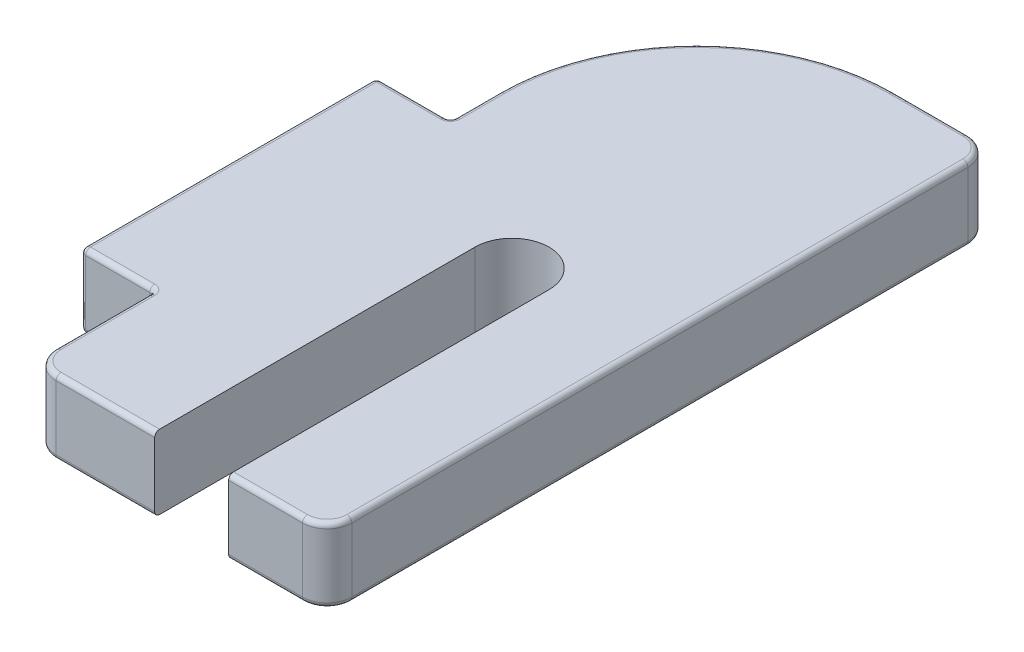
SolidWorks part; units mm, degrees
ref_plane "Front Plane" through (0, 0, 0) normal (0, 0, 1) x (1, 0, 0)
ref_plane "Top Plane" through (0, 0, 0) normal (0, 1, 0) x (1, 0, 0)
ref_plane "Right Plane" through (0, 0, 0) normal (1, 0, 0) x (0, 0, -1)
sketch "Sketch1" plane through (0, 0, 0) normal (0, 1, 0) x (1, 0, 0)
  line L0 (-1.5, 0) -> (-1.5, -13)
  line L1 (1.5, 0) -> (1.5, -13)
  line L2 (1.5, -13) -> (4.5, -13)
  line L3 (5.5, -12) -> (5.5, 13)
  line L4 (4.5, 14) -> (1.5, 14)
  line L5 (-6.5, 6) -> (-6.5, 4)
  line L6 (-6.5, 4) -> (-9.5, 4)
  line L7 (-9.5, 4) -> (-9.5, -8)
  line L8 (-9.5, -8) -> (-6.5, -8)
  line L9 (-6.5, -8) -> (-6.5, -12)
  line L10 (-5.5, -13) -> (-1.5, -13)
  arc A0 (1.5, 0) -> (-1.5, 0) centre (0, 0) ccw
  arc A1 (1.5, 14) -> (-6.5, 6) centre (1.5, 6) ccw
  arc A2 (-6.5, -12) -> (-5.5, -13) centre (-5.5, -12) ccw
  arc A3 (4.5, -13) -> (5.5, -12) centre (4.5, -12) ccw
  arc A4 (5.5, 13) -> (4.5, 14) centre (4.5, 13) ccw
  point P18 (-6.5, -13)
  point P21 (5.5, -13)
  point P24 (5.5, 14)
  dimension "D1" = 1.5
  dimension "D9" = 8
  dimension "D10" = 1
  dimension "D2" = 4
  dimension "D3" = 5
  dimension "D4" = 27
  dimension "D5" = 13
  dimension "D6" = 12
  dimension "D7" = 5
  dimension "D8" = 3
extrude "Boss-Extrude1" add sketch "Sketch1" along normal blind 3
fillet "Fillet1" radius 0.2 30 edges at (-8, 0, 8) (-8, 3, 8) (-8, 0, -4) (-8, 3, -4) (-6.5, 0, 10) (-6.2071, 0, 12.7071) (-6.5, 3, 10) (-6.2071, 3, 12.7071) (3, 0, 13) (5.2071, 0, 12.7071) (-6.5, 0, -5) (-4.1569, 0, -11.6569) (3, 0, -14) (5.2071, 0, -13.7071) (3, 3, 13) (5.2071, 3, 12.7071) (-6.5, 3, -5) (-4.1569, 3, -11.6569) (3, 3, -14) (5.2071, 3, -13.7071) (-9.5, 1.5, -4) (-9.5, 3, 2) (-9.5, 1.5, 8) (-9.5, 0, 2) (-6.5, 1.5, -4) (-6.5, 1.5, 8) (-3.5, 0, 13) (-3.5, 3, 13) (5.5, 0, -0.5) (5.5, 3, -0.5)
ref_plane "Plane1" through (0, 0, 0) normal (0, 0, 1) x (0, -1, 0)
